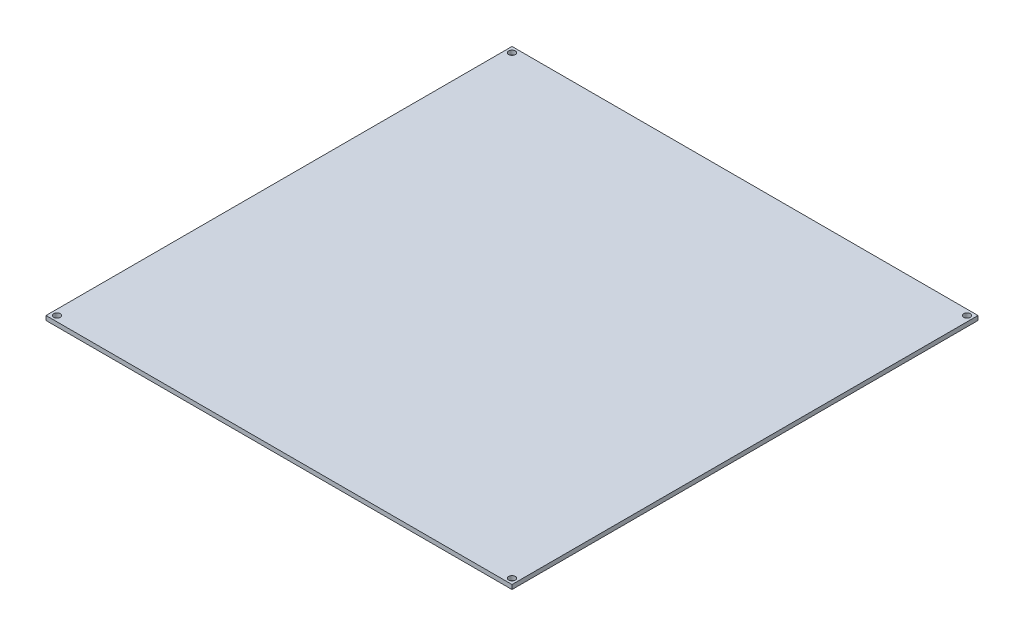
SolidWorks part; units mm, degrees
ref_plane "Front" through (0, 0, 0) normal (0, 0, 1) x (1, 0, 0)
ref_plane "Top" through (0, 0, 0) normal (0, 1, 0) x (1, 0, 0)
ref_plane "Right" through (0, 0, 0) normal (1, 0, 0) x (0, 0, -1)
sketch "Sketch1" plane through (0, 0, 0) normal (0, 1, 0) x (1, 0, 0)
  line L0 (-107, 107) -> (-107, -107)
  line L1 (-107, -107) -> (107, -107)
  line L2 (107, -107) -> (107, 107)
  line L3 (107, 107) -> (-107, 107)
  circle A0 centre (-104.5, 104.5) radius 1.5
  circle A1 centre (104.5, 104.5) radius 1.5
  circle A2 centre (104.5, -104.5) radius 1.5
  circle A3 centre (-104.5, -104.5) radius 1.5
extrude "Boss-Extrude1" add sketch "Sketch1" along normal blind 2
sketch "Sketch2" plane through (0, 2, 0) normal (0, 1, 0) x (1, 0, 0)
  line L0 (-59.9313, 33.8067) -> (140.0687, 33.8067) construction
  line L1 (-56.9999, 37.0001) -> (143.0001, 37.0001) construction
